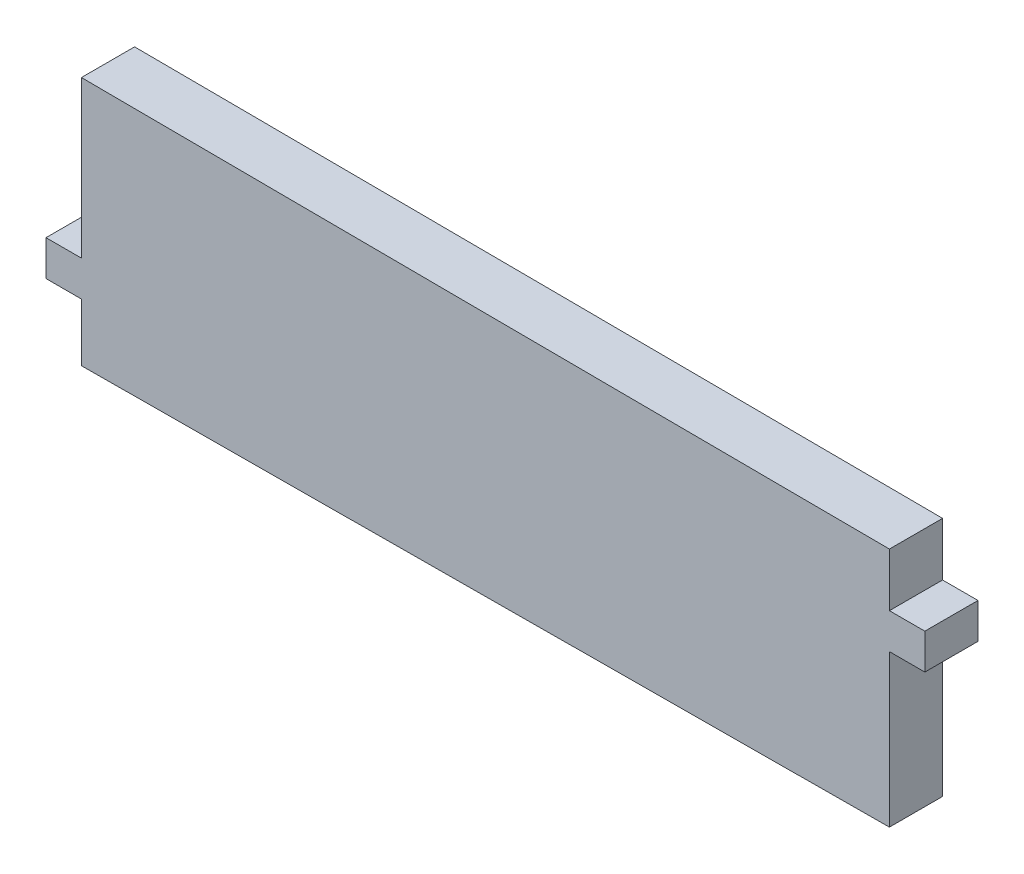
SolidWorks part; units mm, degrees
material "Balsa"
ref_plane "Front Plane" through (0, 0, 0) normal (0, 0, 1) x (1, 0, 0)
ref_plane "Top Plane" through (0, 0, 0) normal (0, 1, 0) x (1, 0, 0)
ref_plane "Right Plane" through (0, 0, 0) normal (1, 0, 0) x (0, 0, -1)
sketch "Sketch1" plane through (0, 0, 0) normal (0, 0, 1) x (1, 0, 0)
  line L0 (84.6718, -9.7949) -> (81.4968, -9.7949)
  line L1 (81.4968, -9.7949) -> (81.4968, -6.6199)
  line L2 (81.4968, -6.6199) -> (84.6718, -6.6199)
  line L3 (84.6718, -6.6199) -> (84.6718, 7.3931)
  line L4 (84.6718, -9.7949) -> (84.6718, -14.9693)
  line L5 (157.0618, 2.2193) -> (160.2368, 2.2193)
  line L6 (160.2368, 2.2193) -> (160.2368, -0.9557)
  line L7 (160.2368, -0.9557) -> (157.0618, -0.9557)
  line L8 (157.0618, -0.9557) -> (157.0618, -14.578)
  line L9 (157.0618, -14.578) -> (84.6718, -14.9693)
  line L10 (157.0618, 2.2193) -> (157.0618, 7.0022)
  line L11 (157.0618, 7.0022) -> (84.6718, 7.3931)
extrude "Boss-Extrude1" add sketch "Sketch1" along normal up to surface (4.7625 mm away)
